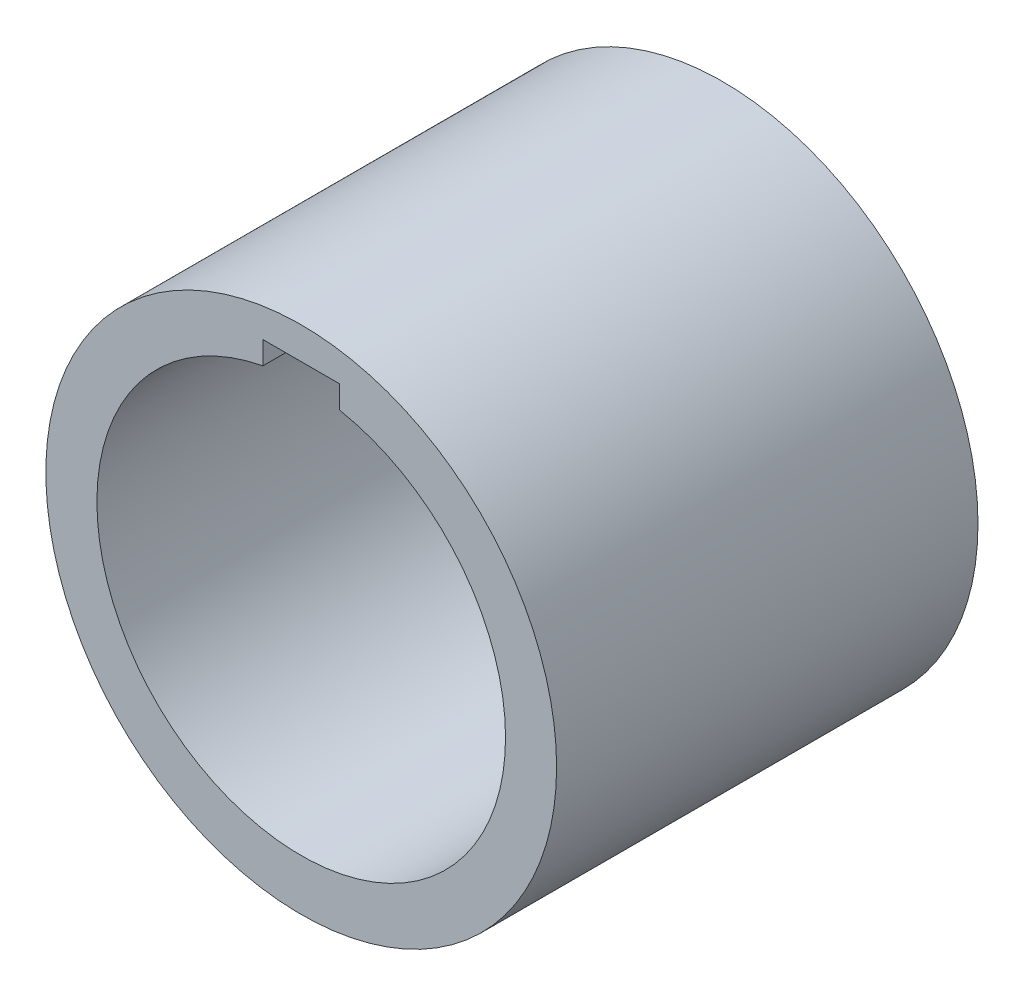
SolidWorks part; units mm, degrees
ref_plane "Alzado" through (0, 0, 0) normal (0, 0, 1) x (1, 0, 0)
ref_plane "Planta" through (0, 0, 0) normal (0, 1, 0) x (1, 0, 0)
ref_plane "Vista lateral" through (0, 0, 0) normal (1, 0, 0) x (0, 0, -1)
sketch "Croquis1" plane through (0, 0, 0) normal (0, 0, 1) x (1, 0, 0)
  circle A0 centre (0, 0) radius 7.8 construction
  circle A1 centre (0, 0) radius 10
  dimension "D1" = 15.6
  dimension "D2" = 20
extrude "Saliente-Extruir1" add sketch "Croquis1" along normal blind 1.5
sketch "Croquis2" plane through (0, 0, 1.5) normal (0, 0, 1) x (1, 0, 0)
  circle A0 centre (0, 0) radius 10
  circle A1 centre (0, 0) radius 8
  dimension "D1" = 20
  dimension "D2" = 16
extrude "Saliente-Extruir2" add sketch "Croquis2" along normal blind 15
sketch "Croquis4" plane through (0, 0, 1.5) normal (0, 0, 1) x (1, 0, 0)
  arc A0 (-0.7083, -6.0115) -> (0.8915, -5.9871) centre (0.0916, -5.9993) ccw construction
  arc A1 (-6.0115, 0.7083) -> (-5.9871, -0.8915) centre (-5.9993, -0.0916) ccw construction
  arc A2 (0.7083, 6.0115) -> (-0.8915, 5.9871) centre (-0.0916, 5.9993) ccw construction
  arc A3 (6.0115, -0.7083) -> (5.9871, 0.8915) centre (5.9993, 0.0916) ccw construction
  circle A4 centre (0.0916, -5.9993) radius 0.8 construction
  circle A5 centre (-5.9993, -0.0916) radius 0.8 construction
  circle A6 centre (-0.0916, 5.9993) radius 0.8 construction
  circle A7 centre (5.9993, 0.0916) radius 0.8 construction
  circle A8 centre (-5.9993, -0.0916) radius 0.95
  circle A9 centre (-0.0916, 5.9993) radius 0.95
  circle A10 centre (5.9993, 0.0916) radius 0.95
  circle A11 centre (0.0916, -5.9993) radius 0.95
  dimension "D1" = 0.15
extrude "Cortar-Extruir2" cut sketch "Croquis4" against normal up to next
sketch "Croquis5" plane through (0, 0, 16.5) normal (0, 0, 1) x (1, 0, 0)
  line L0 (0, 8) -> (0, -8) construction
  line L2 (-1.5, 7.25) -> (1.5, 7.25)
  line L3 (-1.5, 7.25) -> (-1.5, 8.75)
  line L4 (-1.5, 8.75) -> (1.5, 8.75)
  line L5 (1.5, 7.25) -> (1.5, 8.75)
  line L6 (0, 8.75) -> (0, 7.25) construction
  line L7 (-1.5, 8) -> (1.5, 8) construction
  circle A0 centre (0, 0) radius 8 construction
  circle A1 centre (0, 0) radius 8 construction
  dimension "D1" = 3
  dimension "D2" = 0.75
extrude "Cortar-Extruir3" cut sketch "Croquis5" against normal up to surface (15 mm away) up to face at (-5.0493, -0.0916, 1.5)
sketch "Croquis6" plane through (0, 0, 1.5) normal (0, 0, 1) x (1, 0, 0)
  line L3 (1.5, 7.8581) -> (1.5, 8.75)
  line L4 (1.5, 8.75) -> (-1.5, 8.75)
  line L5 (-1.5, 8.75) -> (-1.5, 7.8581)
  line L6 (1.5, 7.8581) -> (1.5, 8.75)
  line L7 (1.5, 8.75) -> (-1.5, 8.75)
  line L8 (-1.5, 8.75) -> (-1.5, 7.8581)
  circle A0 centre (5.9993, 0.0916) radius 0.95 construction
  arc A1 (-1.5, 7.8581) -> (1.5, 7.8581) centre (0, 0) ccw
  arc A2 (-1.5, 7.8581) -> (1.5, 7.8581) centre (0, 0) ccw
  circle A3 centre (0.0916, -5.9993) radius 0.95 construction
  circle A4 centre (-5.9993, -0.0916) radius 0.95 construction
  circle A5 centre (-0.0916, 5.9993) radius 0.95 construction
  circle A6 centre (5.9993, 0.0916) radius 0.95 construction
  circle A7 centre (0.0916, -5.9993) radius 0.95 construction
  circle A8 centre (-5.9993, -0.0916) radius 0.95 construction
  circle A9 centre (-0.0916, 5.9993) radius 0.95 construction
  circle A10 centre (0, 0) radius 3
  circle A11 centre (-0.0916, 5.9993) radius 1.45
  circle A12 centre (5.9993, 0.0916) radius 1.45
  circle A13 centre (-5.9993, -0.0916) radius 1.45
  circle A14 centre (0.0916, -5.9993) radius 1.45
  dimension "D2" = 6
  dimension "D1" = 0
  dimension "D3" = 0.5
extrude "Saliente-Extruir3" add sketch "Croquis6" along normal blind 2
